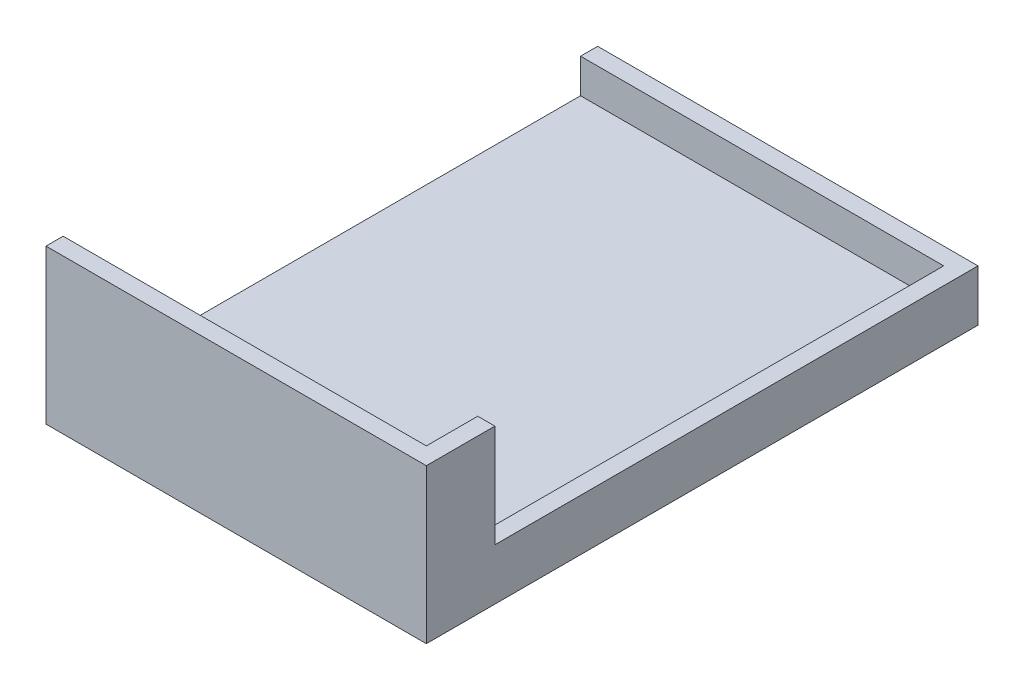
SolidWorks part; units mm, degrees
ref_plane "Front Plane" through (0, 0, 0) normal (0, 0, 1) x (1, 0, 0)
ref_plane "Top Plane" through (0, 0, 0) normal (0, 1, 0) x (1, 0, 0)
ref_plane "Right Plane" through (0, 0, 0) normal (1, 0, 0) x (0, 0, -1)
sketch "Sketch1" plane through (0, 0, 0) normal (0, 1, 0) x (1, 0, 0)
  line L1 (-31.635, -47.885) -> (32.5, -47.885) construction
  line L2 (-31.635, -47.885) -> (-31.635, 48) construction
  line L3 (-31.635, 48) -> (32.5, 48) construction
  line L4 (32.5, -47.885) -> (32.5, 48) construction
  line L5 (-34.81, -51.06) -> (35.675, -51.06)
  line L6 (-34.81, -51.06) -> (-34.81, 51.175)
  line L7 (-34.81, 51.175) -> (35.675, 51.175)
  line L8 (35.675, -51.06) -> (35.675, 51.175)
  point P0 (0, 0)
  point P6 (0, 0)
  dimension "D1" = 64.135
  dimension "D2" = 95.885
  dimension "D3" = 3.175
  dimension "D4" = 3.175
  dimension "D5" = 3.175
  dimension "D6" = 3.175
extrude "Boss-Extrude1" add sketch "Sketch1" along normal blind 28.575
shell "Shell1" thickness 3.175
sketch "Sketch2" plane through (35.675, 0, 0) normal (1, 0, 0) x (0, 0, -1)
  line L0 (-51.06, 28.575) -> (51.175, 28.575) construction
  line L1 (-38.36, 28.575) -> (51.175, 28.575)
  line L2 (-38.36, 28.575) -> (-38.36, 9.525)
  line L3 (-38.36, 9.525) -> (51.175, 9.525)
  line L4 (51.175, 28.575) -> (51.175, 9.525)
  line L5 (-51.06, 28.575) -> (-51.06, 0) construction
  line L6 (51.175, 28.575) -> (51.175, 0) construction
  dimension "D1" = 12.7
  dimension "D2" = 0
  dimension "D3" = 19.05
extrude "Cut-Extrude1" cut sketch "Sketch2" against normal up to surface (3.175 mm away) up to face at (32.5, 15.875, -0.0575)
sketch "Sketch3" plane through (0, 0, -51.175) normal (0, 0, -1) x (-1, 0, 0)
  line L0 (-35.675, 9.525) -> (-35.675, 0) construction
  line L1 (34.81, 28.575) -> (-32.5, 28.575)
  line L2 (34.81, 28.575) -> (34.81, 9.525)
  line L3 (34.81, 9.525) -> (-32.5, 9.525)
  line L4 (-32.5, 28.575) -> (-32.5, 9.525)
  dimension "D1" = 3.175
  dimension "D2" = 19.05
extrude "Cut-Extrude2" cut sketch "Sketch3" against normal up to surface (3.175 mm away) up to face at (5.576, 14.605, -48)
